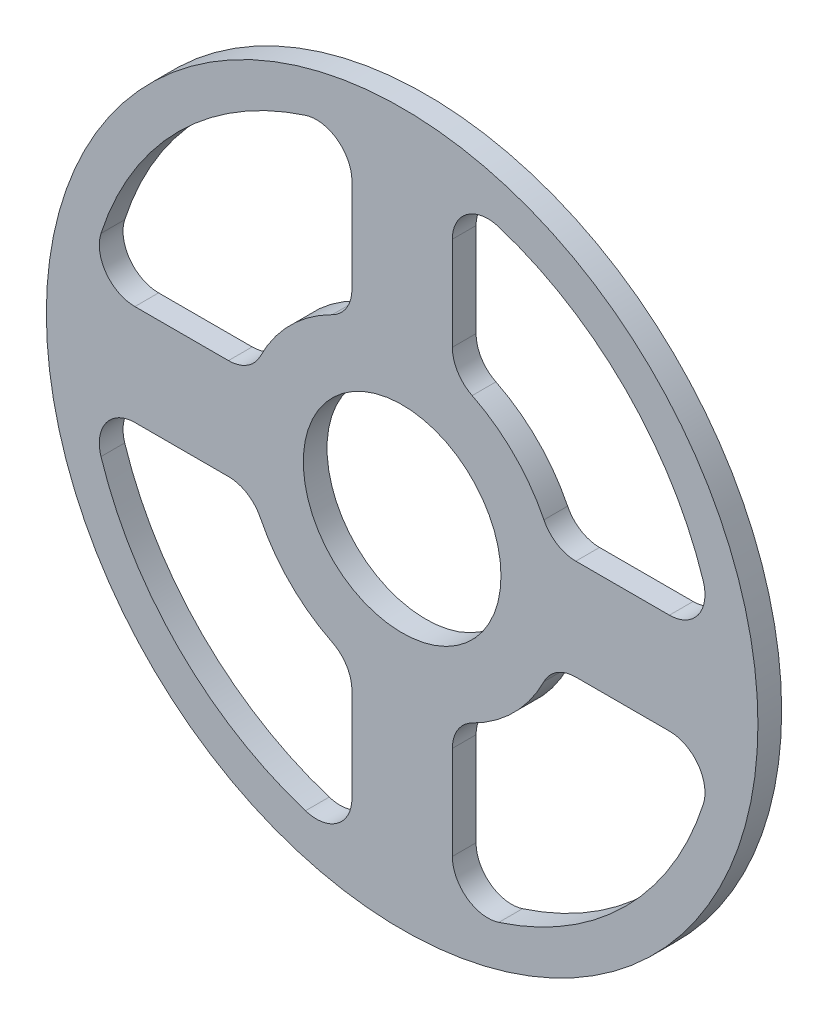
SolidWorks part; units mm, degrees
ref_plane "정면" through (0, 0, 0) normal (0, 0, 1) x (1, 0, 0)
ref_plane "윗면" through (0, 0, 0) normal (0, 1, 0) x (1, 0, 0)
ref_plane "우측면" through (0, 0, 0) normal (1, 0, 0) x (0, 0, -1)
sketch "스케치1" plane through (0, 0, 0) normal (0, 0, 1) x (1, 0, 0)
  circle A0 centre (0, 0) radius 45
  circle A1 centre (0, 0) radius 12.5
  dimension "D1" = 90
  dimension "D2" = 25
extrude "보스-돌출1" add sketch "스케치1" along normal mid plane 3
sketch "스케치2" plane through (0, 0, 1.5) normal (0, 0, 1) x (1, 0, 0)
  line L0 (0, 45) -> (0, 0) construction
  line L1 (0, 0) -> (45, 0) construction
  line L2 (6.35, 39.4928) -> (6.35, 18.9652)
  line L3 (18.9652, 6.35) -> (39.4928, 6.35)
  line L4 (6.35, 45) -> (6.35, 6.35) construction
  line L5 (6.35, 6.35) -> (45, 6.35) construction
  circle A0 centre (0, 0) radius 45 construction
  arc A1 (18.9652, 6.35) -> (6.35, 18.9652) centre (0, 0) ccw
  arc A2 (39.4928, 6.35) -> (6.35, 39.4928) centre (0, 0) ccw
  dimension "D2" = 40
  dimension "D3" = 20
  dimension "D1" = 6.35
extrude "컷-돌출1" cut sketch "스케치2" against normal through all
fillet "필렛1" radius 4.5 4 edges at (6.35, 39.4928, 0) (39.4928, 6.35, 0) (18.9652, 6.35, 0) (6.35, 18.9652, 0)
pattern_circular "원형 패턴1" count 4 over 360 about axis through (0, 0, 0) along (0, 0, 1) of "컷-돌출1", "필렛1"
